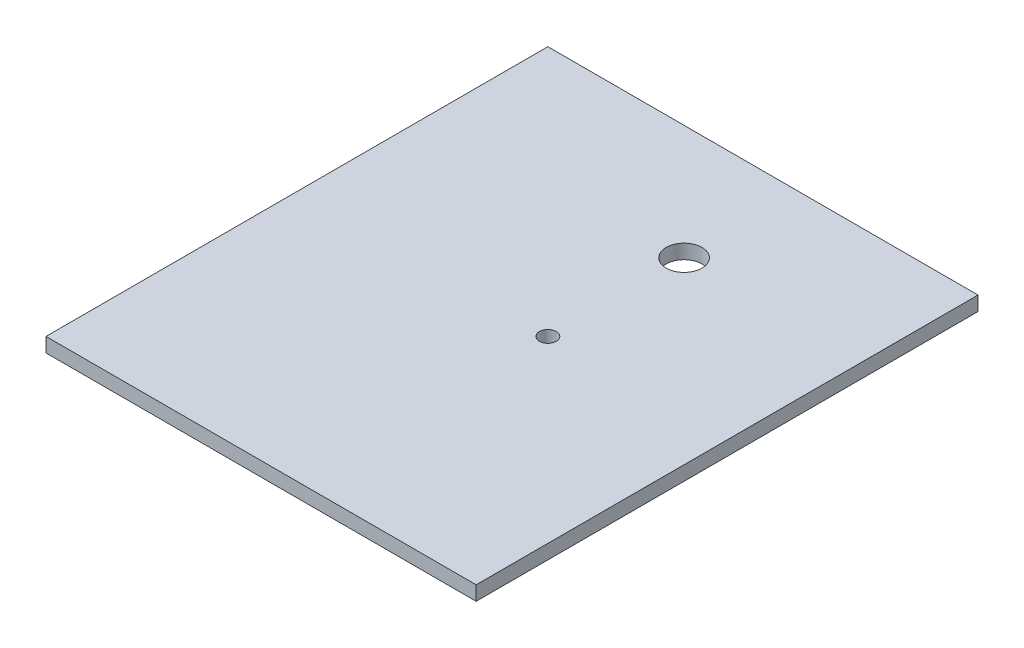
SolidWorks part; units mm, degrees
ref_plane "Front Plane" through (0, 0, 0) normal (0, 0, 1) x (1, 0, 0)
ref_plane "Top Plane" through (0, 0, 0) normal (0, 1, 0) x (1, 0, 0)
ref_plane "Right Plane" through (0, 0, 0) normal (1, 0, 0) x (0, 0, -1)
sketch "Sketch1" plane through (0, 0, 0) normal (0, 1, 0) x (1, 0, 0)
  line L1 (63.5, 88.9) -> (-88.9, 88.9)
  line L2 (63.5, 88.9) -> (63.5, -88.9)
  line L3 (63.5, -88.9) -> (-88.9, -88.9)
  line L4 (-88.9, 88.9) -> (-88.9, -88.9)
  circle A1 centre (0, 0) radius 2.9972
  circle A2 centre (0, 48.26) radius 6.35
  dimension "D1" = 63.5
  dimension "D2" = 5.9944
  dimension "D3" = 12.7
  dimension "D4" = 48.26
  dimension "D5" = 152.4
  dimension "D6" = 177.8
  dimension "D7" = 88.9
extrude "Boss-Extrude1" add sketch "Sketch1" along normal blind 5.08
